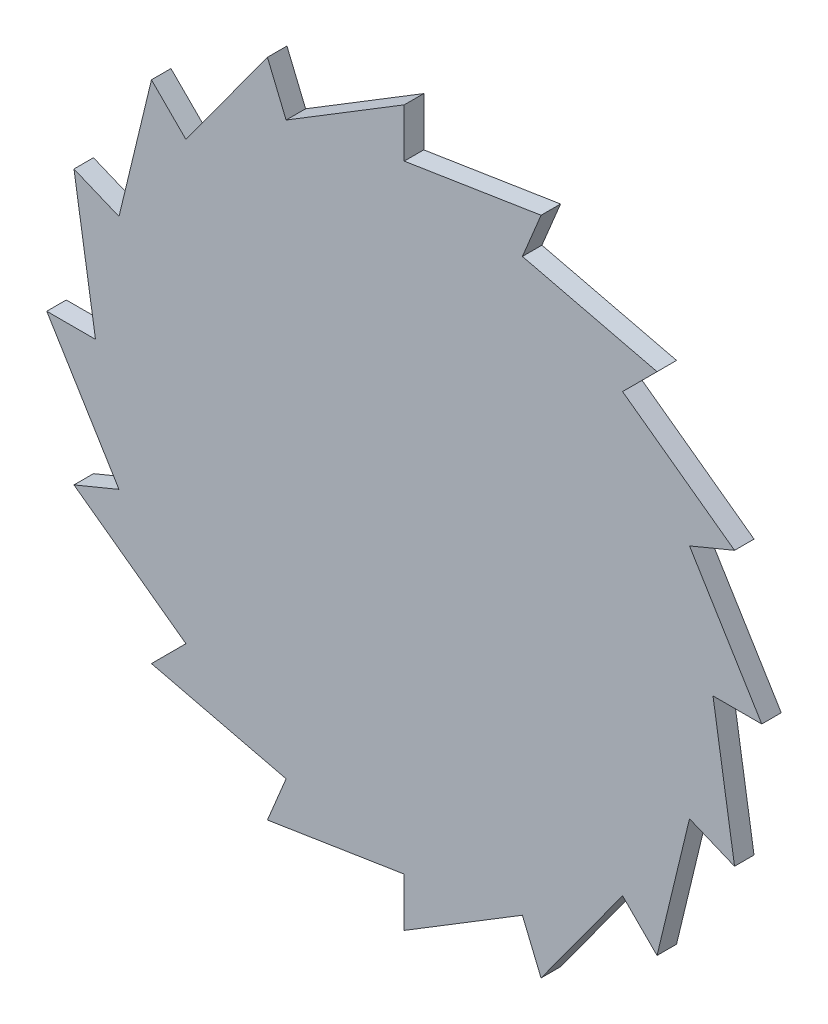
SolidWorks part; units mm, degrees
ref_plane "Front Plane" through (0, 0, 0) normal (0, 0, 1) x (1, 0, 0)
ref_plane "Top Plane" through (0, 0, 0) normal (0, 1, 0) x (1, 0, 0)
ref_plane "Right Plane" through (0, 0, 0) normal (1, 0, 0) x (0, 0, -1)
sketch "Sketch1" plane through (0, 0, 0) normal (0, 0, 1) x (1, 0, 0)
  circle A0 centre (0, 0) radius 55
  dimension "D1" = 110
extrude "Boss-Extrude1" add sketch "Sketch1" along normal blind 3
sketch "Sketch2" plane through (0, 0, 0) normal (0, 0, -1) x (-1, 0, 0)
  line L0 (47.5, 0) -> (55, 0)
  line L1 (43.8843, -18.1775) -> (50.8134, -21.0476)
  line L2 (33.5876, -33.5876) -> (38.8909, -38.8909)
  line L3 (18.1775, -43.8843) -> (21.0476, -50.8134)
  line L4 (0, -47.5) -> (0, -55)
  line L5 (-18.1775, -43.8843) -> (-21.0476, -50.8134)
  line L6 (-33.5876, -33.5876) -> (-38.8909, -38.8909)
  line L7 (-43.8843, -18.1775) -> (-50.8134, -21.0476)
  line L8 (-47.5, 0) -> (-55, 0)
  line L9 (-43.8843, 18.1775) -> (-50.8134, 21.0476)
  line L10 (-33.5876, 33.5876) -> (-38.8909, 38.8909)
  line L11 (-18.1775, 43.8843) -> (-21.0476, 50.8134)
  line L12 (0, 47.5) -> (0, 55)
  line L13 (18.1775, 43.8843) -> (21.0476, 50.8134)
  line L14 (33.5876, 33.5876) -> (38.8909, 38.8909)
  line L15 (43.8843, 18.1775) -> (50.8134, 21.0476)
  line L16 (47.5, 0) -> (50.8134, 21.0476)
  line L17 (43.8843, -18.1775) -> (55, 0)
  line L18 (33.5876, -33.5876) -> (50.8134, -21.0476)
  line L19 (18.1775, -43.8843) -> (38.8909, -38.8909)
  line L20 (0, -47.5) -> (21.0476, -50.8134)
  line L21 (-18.1775, -43.8843) -> (0, -55)
  line L22 (-33.5876, -33.5876) -> (-21.0476, -50.8134)
  line L23 (-43.8843, -18.1775) -> (-38.8909, -38.8909)
  line L24 (-47.5, 0) -> (-50.8134, -21.0476)
  line L25 (-43.8843, 18.1775) -> (-55, 0)
  line L26 (-33.5876, 33.5876) -> (-50.8134, 21.0476)
  line L27 (-18.1775, 43.8843) -> (-38.8909, 38.8909)
  line L28 (0, 47.5) -> (-21.0476, 50.8134)
  line L29 (18.1775, 43.8843) -> (0, 55)
  line L30 (33.5876, 33.5876) -> (21.0476, 50.8134)
  line L31 (43.8843, 18.1775) -> (38.8909, 38.8909)
  circle A0 centre (0, 0) radius 47.5
  circle A1 centre (0, 0) radius 55 construction
  point P40 (0, 0)
  point P71 (0, 0)
  circle M2 centre (0, 0) radius 55
  dimension "D1" = 95
  dimension "D2" = 16
  dimension "D3" = 16
extrude "Cut-Extrude1" cut sketch "Sketch2" against normal blind 3 contours L31 L15 M2 | L30 L14 M2 | L29 L13 M2 | L28 L12 M2 | L27 L11 M2 | L26 L10 M2 | L25 L9 M2 | L24 L8 M2 | L23 L7 M2 | L22 L6 M2 | L21 L5 M2 | L20 L4 M2 | L19 L3 M2 | L18 L2 M2 | L17 L1 M2 | L16 L0 M2
sketch "Sketch3" plane through (0, 0, 0) normal (0, 0, -1) x (-1, 0, 0)
  circle A0 centre (0, 0) radius 47.5
  circle A1 centre (0, 0) radius 47.128
  circle A2 centre (0, 0) radius 2.5
  dimension "D1" = 5
extrude "Cut-Extrude2" cut sketch "Sketch3" against normal blind 2 contours A2
sketch "Sketch4" plane through (0, 0, 3) normal (0, 0, 1) x (1, 0, 0)
  circle A0 centre (0, 0) radius 47.5
  circle A1 centre (0, 0) radius 47.3775
